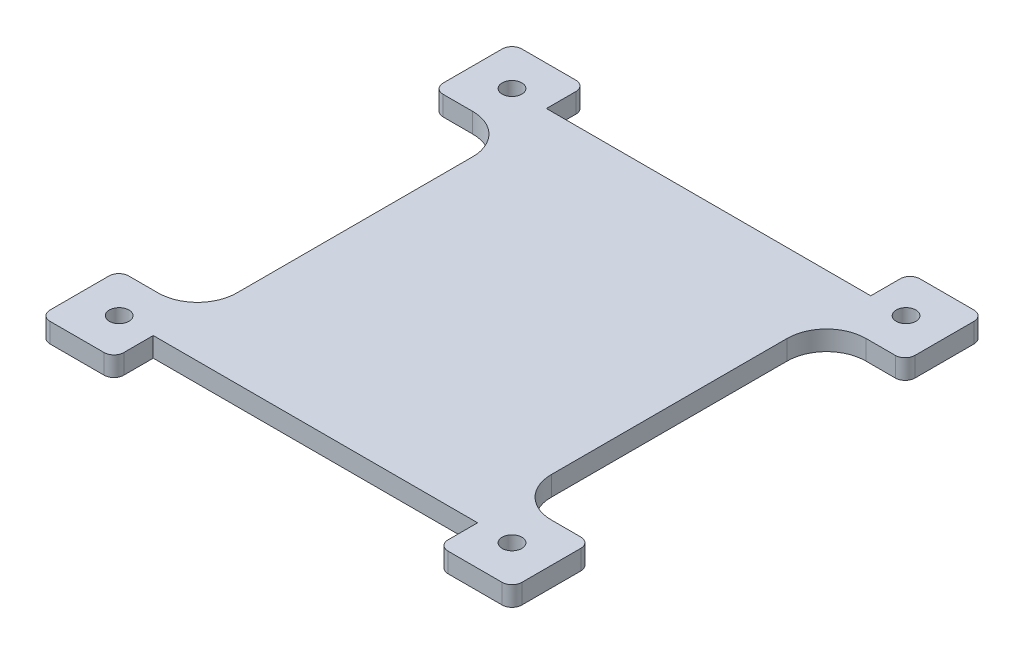
SolidWorks part; units mm, degrees
ref_plane "Front Plane" through (0, 0, 0) normal (0, 0, 1) x (1, 0, 0)
ref_plane "Top Plane" through (0, 0, 0) normal (0, 1, 0) x (1, 0, 0)
ref_plane "Right Plane" through (0, 0, 0) normal (1, 0, 0) x (0, 0, -1)
sketch "Sketch1" plane through (0, 0, 0) normal (0, 1, 0) x (1, 0, 0)
  line L0 (-50.8, 50.8) -> (-50.8, -50.8)
  line L5 (0, 63.5) -> (0, -63.5) construction
  line L6 (-76.2, 76.2) -> (-52.3875, 76.2)
  line L7 (-50.8, 0) -> (50.8, 0) construction
  line L8 (-50.8, 50.8) -> (-76.2, 50.8)
  line L9 (-76.2, 50.8) -> (-76.2, 76.2)
  line L10 (-52.3875, 76.2) -> (-52.3875, 63.5)
  line L11 (-52.3875, 63.5) -> (52.3875, 63.5)
  line L12 (52.3875, 63.5) -> (52.3875, 76.2)
  line L13 (52.3875, 76.2) -> (76.2, 76.2)
  line L14 (76.2, 76.2) -> (76.2, 50.8)
  line L15 (76.2, 50.8) -> (50.8, 50.8)
  line L16 (50.8, 50.8) -> (50.8, -50.8)
  line L17 (-50.8, -50.8) -> (-76.2, -50.8)
  line L18 (-76.2, -50.8) -> (-76.2, -76.2)
  line L20 (76.2, -76.2) -> (76.2, -50.8)
  line L21 (76.2, -50.8) -> (50.8, -50.8)
  line L22 (76.2, -76.2) -> (52.3875, -76.2)
  line L23 (52.3875, -76.2) -> (52.3875, -63.5)
  line L24 (52.3875, -63.5) -> (-52.3875, -63.5)
  line L25 (-52.3875, -63.5) -> (-52.3875, -76.2)
  line L26 (-52.3875, -76.2) -> (-76.2, -76.2)
  circle A0 centre (-63.5485, 63.5485) radius 3.175
  circle A1 centre (63.6455, 63.6455) radius 3.175
  circle A2 centre (63.5485, -63.5485) radius 3.175
  circle A3 centre (-63.4515, -63.4515) radius 3.175
  point P0 (0, 0)
  point P1 (-50.8, 0)
  point P10 (0, 0)
  point P11 (0, 63.5)
  point P32 (0, 0)
  dimension "D10" = 6.35
  dimension "D1" = 127
  dimension "D2" = 152.4
  dimension "D3" = 101.6
  dimension "D4" = 101.6
  dimension "D5" = 104.775
  dimension "D6" = 152.4
  dimension "D8" = 127
  dimension "D9" = 127
extrude "Boss-Extrude1" add sketch "Sketch1" along normal blind 6.35 contours L6 L10 L11 L12 L13 L14 L15 L16 L21 L20 L22 L23 L24 L25 L26 L18 L17 L0 L8 L9
fillet "Fillet1" radius 12.7 4 edges at (50.8, 3.175, -50.8) (50.8, 3.175, 50.8) (-50.8, 3.175, 50.8) (-50.8, 3.175, -50.8)
fillet "Fillet2" radius 3.175 12 edges at (-76.2, 3.175, -50.8) (-76.2, 3.175, 76.2) (-52.3875, 3.175, 76.2) (52.3875, 3.175, 76.2) (76.2, 3.175, -50.8) (76.2, 3.175, 76.2) (76.2, 3.175, 50.8) (-76.2, 3.175, 50.8) (-76.2, 3.175, -76.2) (76.2, 3.175, -76.2) (52.3875, 3.175, -76.2) (-52.3875, 3.175, -76.2)
